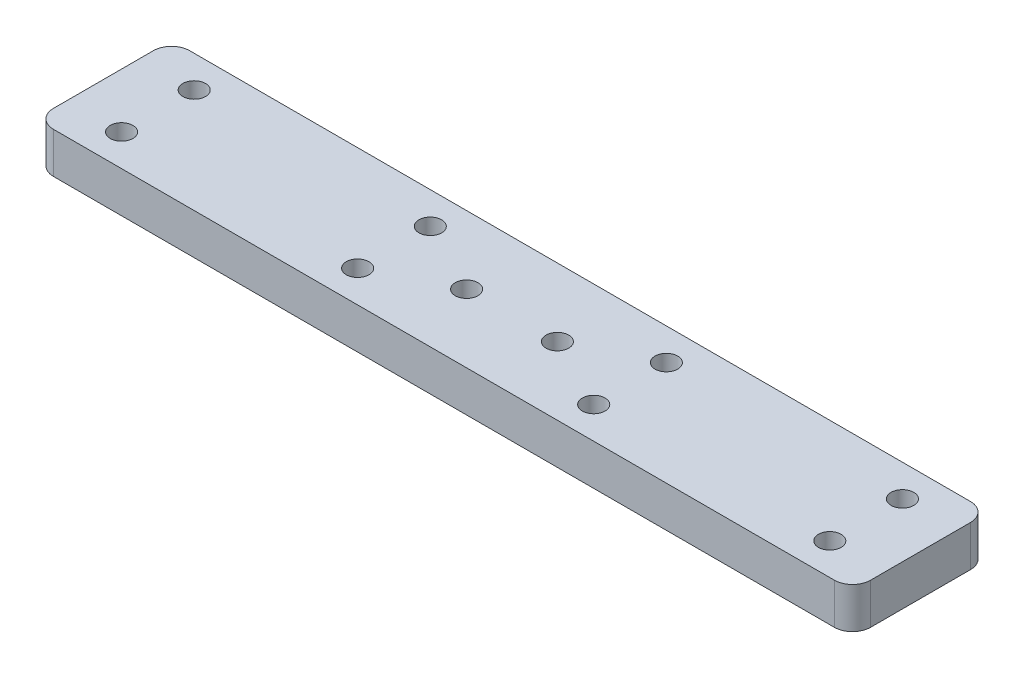
SolidWorks part; units mm, degrees
ref_plane "前视基准面" through (0, 0, 0) normal (0, 0, 1) x (1, 0, 0)
ref_plane "上视基准面" through (0, 0, 0) normal (0, 1, 0) x (1, 0, 0)
ref_plane "右视基准面" through (0, 0, 0) normal (1, 0, 0) x (0, 0, -1)
sketch "草图1" plane through (0, 0, 0) normal (0, 1, 0) x (1, 0, 0)
  line L0 (-5, 0) -> (5, 0) construction
  line L1 (-43, 7.5) -> (43, 7.5)
  line L2 (-45, 5.5) -> (-45, -5.5)
  line L3 (-43, -7.5) -> (43, -7.5)
  line L4 (45, 5.5) -> (45, -5.5)
  line L5 (-45, 7.5) -> (45, -7.5) construction
  line L6 (-45, -7.5) -> (45, 7.5) construction
  line L7 (-39, 4) -> (-39, -4) construction
  line L8 (0, 0) -> (-39, 0) construction
  circle A0 centre (-5, 0) radius 1.25
  circle A1 centre (5, 0) radius 1.25
  circle A2 centre (-39, 4) radius 1.25
  circle A3 centre (-39, -4) radius 1.25
  circle A4 centre (-13, -4) radius 1.25
  circle A5 centre (-13, 4) radius 1.25
  circle A6 centre (13, -4) radius 1.25
  circle A7 centre (13, 4) radius 1.25
  circle A8 centre (39, -4) radius 1.25
  circle A9 centre (39, 4) radius 1.25
  arc A10 (45, 5.5) -> (43, 7.5) centre (43, 5.5) ccw
  arc A11 (45, -5.5) -> (43, -7.5) centre (43, -5.5) cw
  arc A12 (-45, -5.5) -> (-43, -7.5) centre (-43, -5.5) ccw
  arc A13 (-45, 5.5) -> (-43, 7.5) centre (-43, 5.5) cw
  point P0 (0, 0)
  dimension "D4" = 2.5
  dimension "D7" = 2.5
  dimension "D9" = 2
  dimension "D1" = 15
  dimension "D2" = 90
  dimension "D3" = 10
  dimension "D5" = 39
  dimension "D6" = 8
  dimension "D8" = 4
extrude "凸台-拉伸1" add sketch "草图1" along normal blind 4.5
